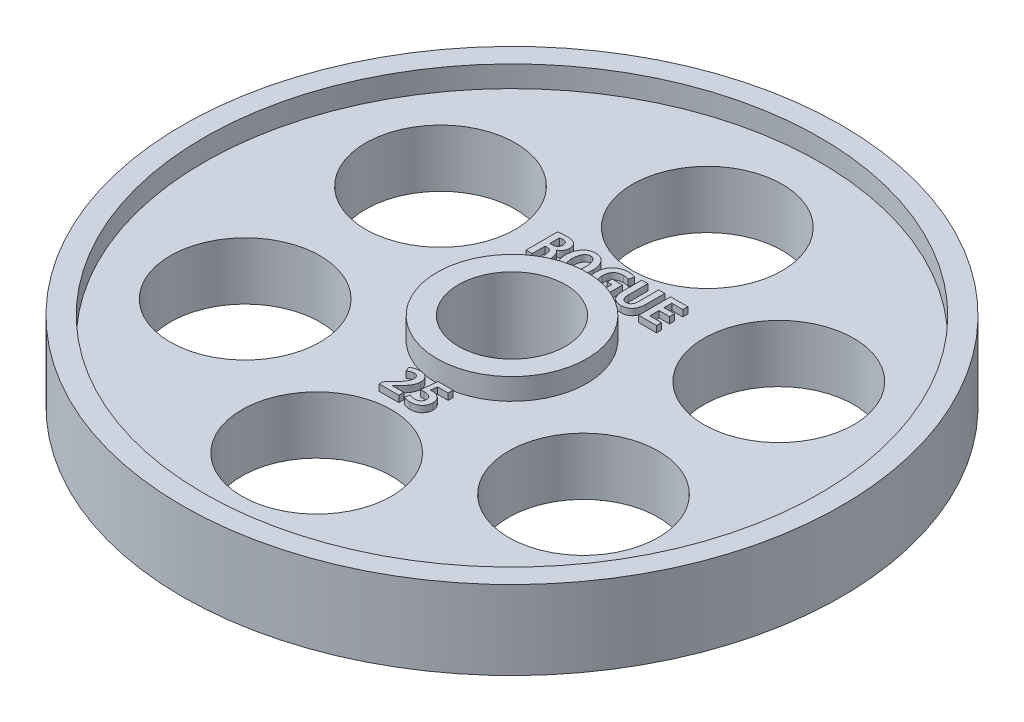
SolidWorks part; units mm, degrees
ref_plane "Front Plane" through (0, 0, 0) normal (0, 0, 1) x (1, 0, 0)
ref_plane "Top Plane" through (0, 0, 0) normal (0, 1, 0) x (1, 0, 0)
ref_plane "Right Plane" through (0, 0, 0) normal (1, 0, 0) x (0, 0, -1)
sketch "Sketch1" plane through (0, 0, 0) normal (0, 1, 0) x (1, 0, 0)
  circle A0 centre (0, 0) radius 154
  circle A1 centre (0, 0) radius 25
  dimension "D1" = 50
  dimension "D2" = 308
extrude "Boss-Extrude1" add sketch "Sketch1" along normal mid plane 36.83
sketch "Sketch2" plane through (0, 18.415, 0) normal (0, 1, 0) x (1, 0, 0)
  circle A0 centre (0, 0) radius 144
  circle A1 centre (0, 0) radius 35
  circle A2 centre (0, 0) radius 154 construction
  dimension "D1" = 10
  dimension "D2" = 35
extrude "Cut-Extrude2" cut sketch "Sketch2" against normal blind 10
sketch "Sketch3" plane through (0, 8.415, 0) normal (0, 1, 0) x (1, 0, 0)
  circle A0 centre (0, 91.2726) radius 35
  circle A1 centre (79.0444, 45.6363) radius 35
  circle A2 centre (79.0444, -45.6363) radius 35
  circle A3 centre (0, -91.2726) radius 35
  circle A4 centre (-79.0444, -45.6363) radius 35
  circle A5 centre (-79.0444, 45.6363) radius 35
  point P14 (0, 0)
  dimension "D1" = 70
  dimension "D2" = 6
extrude "Cut-Extrude3" cut sketch "Sketch3" against normal through all both and the other way through all
sketch "Sketch4" plane through (0, 8.415, 0) normal (0, 1, 0) x (1, 0, 0)
  text T0 "ROGUE" font "Adobe Gothic Std B" height in points 48
  text T1 "25" font "Adobe Gothic Std B" height in points 48
extrude "Boss-Extrude2" add sketch "Sketch4" along normal blind 3
